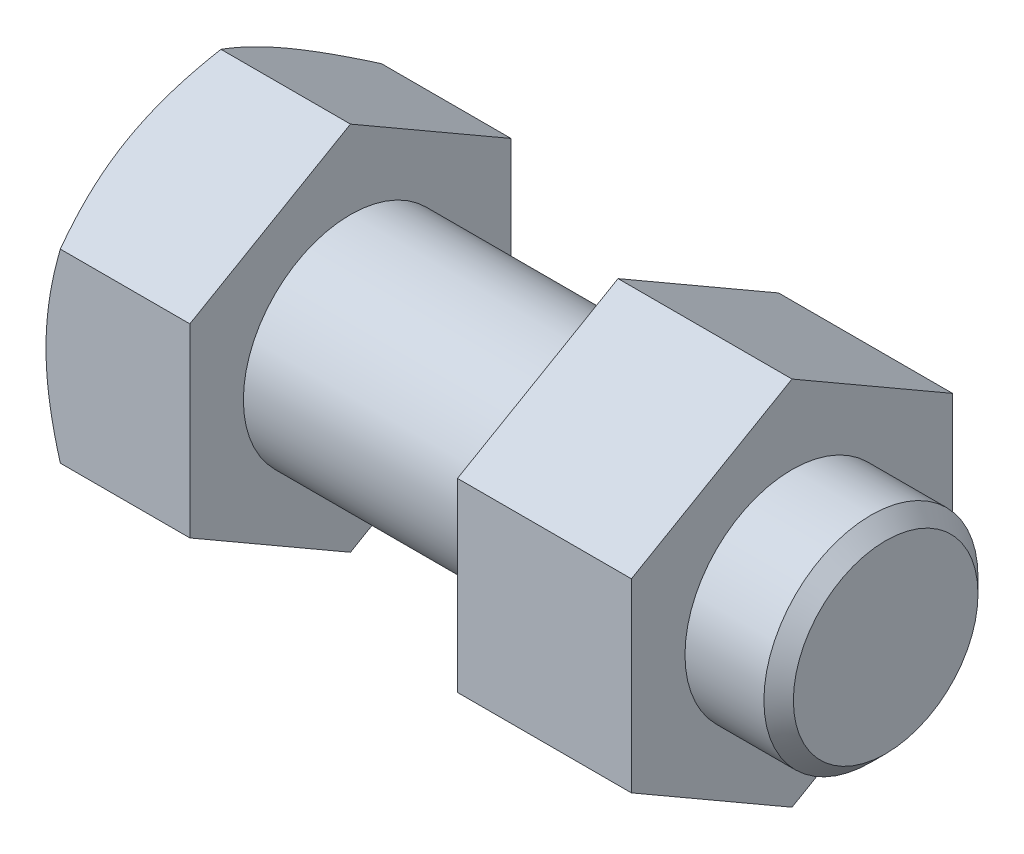
SolidWorks part; units mm, degrees
extrude "BaseHead" add sketch "Sketch1" along normal blind 10.75
sketch "Sketch1" plane through (0, 0, 0) normal (1, 0, 0) x (0, 0, -1)
  line L0 (12, 6.9282) -> (12, -6.9282)
  line L1 (-12, 6.9282) -> (-12, -6.9282)
  line L2 (12, -6.9282) -> (0, -13.8564)
  line L3 (0, -13.8564) -> (-12, -6.9282)
  line L4 (12, 6.9282) -> (0, 13.8564)
  line L5 (0, 13.8564) -> (-12, 6.9282)
  dimension "Width_flats" = 24
  dimension "D2" = 120
  dimension "D3" = 12
  dimension "D4" = 12
  dimension "D5" = 12
material "Dacromet"
ref_plane "Plane1" through (0, 0, 0) normal (0, 0, 1) x (1, 0, 0)
ref_plane "Plane2" through (0, 0, 0) normal (0, 1, 0) x (1, 0, 0)
ref_plane "Plane3" through (0, 0, 0) normal (1, 0, 0) x (0, 0, -1)
sketch "BodySke" plane through (0, 0, 0) normal (0, 0, 1) x (1, 0, 0)
  line L0 (0, 6.9282) -> (0, -6.9282) construction
  line L1 (0, 0) -> (50.75, 0)
  line L2 (0, 0) -> (0, 8)
  line L3 (0, 8) -> (49.6485, 8)
  line L4 (50.75, 0) -> (50.75, 6.8985)
  line L5 (10.75, 13.8564) -> (10.75, 6.9282) construction
  line L6 (50.75, 6.8985) -> (49.6485, 8)
  line L7 (0, 0) -> (96.52, 0) construction
  line L8 (50.75, -6.8985) -> (49.6485, -8) construction
  line L9 (0, -8) -> (49.6485, -8) construction
  line L10 (12.75, 15.24) -> (12.75, -1.27) construction
  line L11 (12.75, 15.24) -> (12.75, -1.27) construction
  line L12 (10.75, 6.9282) -> (10.75, -6.9282) construction
  dimension "Diameter" = 16
  dimension "Advance" = 2
revolve "BaseBody" add sketch "BodySke"
cosmetic thread "ThreadCosmetic" [suppressed]
fillet "HeadFillet" [suppressed] radius 0.6
sketch "Sketch3" plane through (0, 0, 0) normal (0, 0, 1) x (1, 0, 0)
  line L0 (0, 12) -> (3.9585, 18.8564)
  line L1 (0, 13.8564) -> (0, 6.9282) construction
  line L2 (3.9585, 18.8564) -> (3.9585, 23.8564)
  line L3 (3.9585, 23.8564) -> (-10, 23.8564)
  line L4 (-10, 23.8564) -> (-10, 12)
  line L5 (-10, 12) -> (0, 12)
  line L6 (0, 0) -> (99.06, 0) construction
  line L7 (10.75, 13.8564) -> (0, 13.8564) construction
  dimension "D1" = 12
  dimension "D2" = 5
  dimension "D3" = 10
  dimension "D4" = 5
  dimension "Head_ch_ang" = 30
revolve "HeadChamfer" cut sketch "Sketch3" angle 360 about L6
sketch "ThdSchSke" plane through (0, 0, 0) normal (0, 0, 1) x (1, 0, 0)
  line L0 (12.75, -6.8985) -> (11.9787, -8)
  line L1 (12.75, -6.8985) -> (13.5213, -8)
  line L2 (13.5213, -8) -> (13.5213, -10)
  line L3 (-3.175, 0) -> (5.1513, 0) construction
  line L5 (13.5213, -10) -> (11.9787, -10)
  line L6 (11.9787, -10) -> (11.9787, -8)
  dimension "Thread_minor" = 13.797
  dimension "Diameter" = 16
  dimension "Start" = 12.75
revolve "ThreadSchematic" [suppressed] cut sketch "ThdSchSke" angle 360 about L3
pattern_linear "ThdSchPat" [suppressed]
ref_plane "Plane4" through (30.75, 0, 0) normal (1, 0, 0) x (0, 0, -1)
sketch "Sketch4" plane through (30.75, 0, 0) normal (1, 0, 0) x (0, 0, -1)
  line L1 (0, 13.8564) -> (-12, 6.9282)
  line L2 (-12, 6.9282) -> (-12, -6.9282)
  line L3 (-12, -6.9282) -> (0, -13.8564)
  line L4 (0, -13.8564) -> (12, -6.9282)
  line L5 (12, -6.9282) -> (12, 6.9282)
  line L6 (12, 6.9282) -> (0, 13.8564)
  circle A0 centre (0, 0) radius 12 construction
extrude "Boss-Extrude1" add sketch "Sketch4" along normal blind 13
equation "\"D3@Sketch1\" = \"Width_flats@Sketch1\" / 2"
equation "\"D4@Sketch1\" = \"D3@Sketch1\""
equation "\"D5@Sketch1\" = \"D4@Sketch1\""
equation "\"Thread_minor@ThreadCosmetic\" = \"Minor_dia@BodySke\""
equation "\"D1@Sketch3\" = \"Width_flats@Sketch1\" / 2"
equation "' \"D1@Sketch4\" = \"Width_flats@Sketch1\""
equation "\"Thread_length@ThreadCosmetic\" = ((sgn( (\"Length@BodySke\" - \"Advance@BodySke\" ) - \"Thread_nom@BodySke\" )-1)*( (\"Length@BodySke\" - \"Advance@BodySke\" ) - \"Thread_nom@BodySke\" ))/-2+ \"Thread_nom@BodySke\""
equation "\"Thread_minor@ThdSchSke\" = \"Minor_dia@BodySke\""
equation "\"Diameter@ThdSchSke\" = \"Diameter@BodySke\""
equation "\"Overcut@ThdSchSke\" = \"Diameter@BodySke\" * 1.25"
equation "\"Start@ThdSchSke\" = \"Head_ht@BaseHead\" + \"Length@BodySke\" - \"Thread_length@ThreadCosmetic\"  '---Non-countersunk---"
equation "\"Num_threads@ThdSchPat\" = int( \"Thread_length@ThreadCosmetic\" / \"Advance@BodySke\" + 0.999 )  + 1"
equation "\"Advance@ThdSchPat\" = \"Thread_length@ThreadCosmetic\" /  (\"Num_threads@ThdSchPat\" - 1) 'relax it"
equation "\"Num_threads@ThdSchPat\" = \"Num_threads@ThdSchPat\" - sgn( \"Num_threads@ThdSchPat\" - 1) '---chamfered tips only---"
